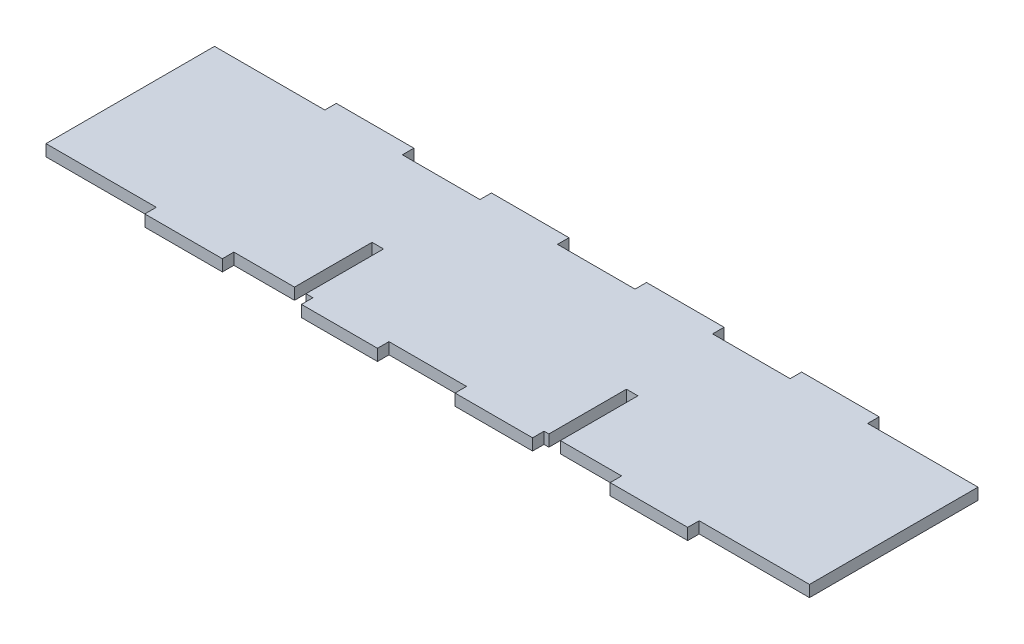
SolidWorks part; units mm, degrees
ref_plane "Front Plane" through (0, 0, 0) normal (0, 0, 1) x (1, 0, 0)
ref_plane "Top Plane" through (0, 0, 0) normal (0, 1, 0) x (1, 0, 0)
ref_plane "Right Plane" through (0, 0, 0) normal (1, 0, 0) x (0, 0, -1)
sketch "Sketch1" plane through (0, 0, 0) normal (0, 1, 0) x (1, 0, 0)
  line L1 (250, 200) -> (-250, 200)
  line L2 (250, 200) -> (250, -200)
  line L3 (250, -200) -> (-250, -200)
  line L4 (-250, 200) -> (-250, -200)
  line L5 (250, 200) -> (-250, -200) construction
  line L6 (250, -200) -> (-250, 200) construction
  point P0 (0, 0)
  dimension "D1" = 500
  dimension "D2" = 400
extrude "Boss-Extrude1" add sketch "Sketch1" along normal blind 6
sketch "Sketch10" plane through (0, 6, 0) normal (0, 1, 0) x (1, 0, 0)
  line B0 (-60.1166, -35.2551) -> (-56.4741, -35.2551)
  line B1 (-56.4741, -35.2551) -> (-56.4741, -41.2551)
  line B2 (-56.4741, -41.2551) -> (-16.7792, -41.2549)
  line B3 (-16.7792, -41.2549) -> (-16.7792, -35.2549)
  line B4 (-16.7792, -35.2549) -> (23.7208, -35.2549)
  line B5 (23.7208, -35.2549) -> (23.7208, -41.2549)
  line B6 (23.7208, -41.2549) -> (64.2208, -41.2549)
  line B7 (64.2208, -41.2549) -> (64.2208, -35.2549)
  line B8 (64.2208, -35.2549) -> (66.7324, -35.2549)
  line B9 (66.7324, 5.2449) -> (72.7325, 5.2449)
  line B10 (72.7325, -35.2549) -> (104.7208, -35.2549)
  line B11 (104.7208, -35.2549) -> (104.7208, -41.2549)
  line B12 (104.7208, -41.2549) -> (145.2208, -41.2549)
  line B13 (145.2208, -41.2549) -> (145.2208, -35.2549)
  line B14 (145.2208, -35.2549) -> (185.7208, -35.2549)
  line B15 (185.7208, -35.2549) -> (202.8258, -35.2549)
  line B16 (202.8258, -35.2549) -> (202.8258, -11.5049)
  line B17 (202.8258, -11.5049) -> (202.8258, 28.9951)
  line B18 (202.8258, 28.9951) -> (202.8258, 52.7451)
  line B19 (202.8258, 52.7451) -> (145.2208, 52.7451)
  line B20 (145.2208, 52.7451) -> (145.2208, 58.7451)
  line B21 (145.2208, 58.7451) -> (104.7208, 58.7451)
  line B22 (104.7208, 58.7451) -> (104.7208, 52.7451)
  line B23 (104.7208, 52.7451) -> (64.2208, 52.7451)
  line B24 (64.2208, 52.7451) -> (64.2208, 58.7451)
  line B25 (64.2208, 58.7451) -> (23.7208, 58.7451)
  line B26 (23.7208, 58.7451) -> (23.7208, 52.7451)
  line B27 (23.7208, 52.7451) -> (-16.7792, 52.7451)
  line B28 (-16.7792, 52.7451) -> (-16.7792, 58.7451)
  line B29 (-16.7792, 58.7451) -> (-57.2792, 58.7451)
  line B30 (-57.2792, 58.7451) -> (-57.2792, 52.7451)
  line B31 (-57.2792, 52.7451) -> (-97.7792, 52.7451)
  line B32 (-97.7792, 52.7451) -> (-97.7792, 58.7451)
  line B33 (-97.7792, 58.7451) -> (-138.2792, 58.7451)
  line B34 (-138.2792, 58.7451) -> (-138.2792, 52.7451)
  line B35 (-138.2792, 52.7451) -> (-178.7792, 52.7451)
  line B36 (-178.7792, 52.7451) -> (-195.8842, 52.7451)
  line B37 (-195.8842, 52.7451) -> (-195.8842, 28.9951)
  line B38 (-195.8842, 28.9951) -> (-195.8842, 28.9949)
  line B39 (-195.8842, 28.9949) -> (-195.8842, -11.5051)
  line B40 (-195.8842, -11.5051) -> (-195.8842, -11.5049)
  line B41 (-195.8842, -11.5049) -> (-195.8842, -35.2549)
  line B42 (-195.8842, -35.2549) -> (-138.2792, -35.2549)
  line B43 (-138.2792, -35.2549) -> (-138.2792, -41.2549)
  line B44 (-138.2792, -41.2549) -> (-97.7792, -41.2549)
  line B45 (-97.7792, -41.2549) -> (-97.7792, -35.2549)
  line B46 (-97.7792, -35.2549) -> (-66.1519, -35.255)
  line B47 (-66.1519, -35.255) -> (-66.1166, -35.2551)
  line B48 (-66.1166, -35.2551) -> (-66.1166, 5.2449)
  line B49 (-66.1166, 5.2449) -> (-60.1166, 5.2449)
  line B50 (-60.1166, 5.2449) -> (-60.1166, -35.2551)
  spline B51 degree 2 poles (66.7324, -35.2549) (66.7324, -35.2551) (66.7324, 5.2449) knots 9 9 9 10 10 10
  spline B52 degree 2 poles (72.7325, 5.2449) (72.7325, -35.2551) (72.7325, -35.2549) knots 11 11 11 12 12 12
  line M2 (-250, 200) -> (-250, -200)
  line M3 (-250, -200) -> (250, -200)
  line M4 (250, -200) -> (250, 200)
  line M5 (250, 200) -> (-250, 200)
sketch_block_instance "Block1-2"
sketch_block "Block1"
extrude "Cut-Extrude4" cut sketch "Sketch10" against normal through all contours B52 B9 B51 B8 B7 B6 B5 B4 B3 B2 B1 B0 B50 B49 B48 B47 B46 B45 B44 B43 B42 B41 B39 B38 B37 B36 B35 B34 B33 B32 B31 B30 B29 B28 B27 B26 B25 B24 B23 B22 B21 B20 B19 B18 B17 M5 M2 M3 M4
